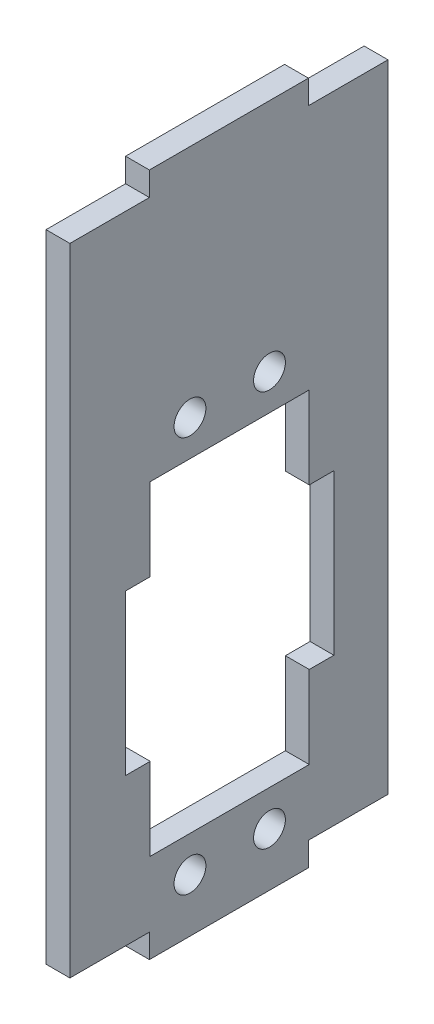
SolidWorks part; units mm, degrees
ref_plane "Plan de face" through (0, 0, 0) normal (0, 0, 1) x (1, 0, 0)
ref_plane "Plan de dessus" through (0, 0, 0) normal (0, 1, 0) x (1, 0, 0)
ref_plane "Plan de droite" through (0, 0, 0) normal (1, 0, 0) x (0, 0, -1)
ref_plane "Plan1" through (3, 0, 0) normal (1, 0, 0) x (0, 0, -1)
sketch "Esquisse1" plane through (3, 0, 0) normal (1, 0, 0) x (0, 0, -1)
  line L12 (-31.5038, 89.2756) -> (-31.5038, 86.2756)
  line L13 (-31.5038, 86.2756) -> (-41.5038, 86.2756)
  line L14 (-41.5038, 86.2756) -> (-41.5038, 6.2756)
  line L15 (-41.5038, 6.2756) -> (-31.5038, 6.2756)
  line L16 (-31.5038, 6.2756) -> (-31.5038, 3.2756)
  line L17 (-31.5038, 3.2756) -> (-11.5038, 3.2756)
  line L18 (-11.5038, 3.2756) -> (-11.5038, 6.2756)
  line L19 (-11.5038, 6.2756) -> (-1.5038, 6.2756)
  line L20 (-1.5038, 6.2756) -> (-1.5038, 86.2756)
  line L21 (-1.5038, 86.2756) -> (-11.5038, 86.2756)
  line L22 (-11.5038, 86.2756) -> (-11.5038, 89.2756)
  line L23 (-11.5038, 89.2756) -> (-31.5038, 89.2756)
  dimension "D2" = 80
  dimension "D3" = 80
  dimension "D4" = 20
  dimension "D5" = 10
  dimension "D6" = 10
  dimension "D7" = 3
  dimension "D8" = 3
  dimension "D13" = 20
  dimension "D14" = 3
  dimension "D15" = 10
  dimension "D16" = 10
  dimension "D17" = 3
extrude "Boss.-Extru.1" add sketch "Esquisse1" against normal blind 3
sketch "Esquisse2" plane through (0, 0, 0) normal (-1, 0, 0) x (0, 0, 1)
  line L0 (11.4038, 44.9256) -> (11.4038, 55.2756)
  line L1 (11.4038, 55.2756) -> (31.4038, 55.2756)
  line L2 (31.4038, 55.2756) -> (31.4038, 44.9256)
  line L3 (31.4038, 44.9256) -> (34.5038, 44.9256)
  line L4 (34.5038, 44.9256) -> (34.5038, 24.8256)
  line L5 (34.5038, 24.8256) -> (31.4038, 24.8256)
  line L6 (31.4038, 24.8256) -> (31.4038, 14.4756)
  line L7 (31.4038, 14.4756) -> (11.4038, 14.4756)
  line L8 (11.4038, 14.4756) -> (11.4038, 24.8256)
  line L9 (11.4038, 24.8256) -> (8.3038, 24.8256)
  line L10 (8.3038, 24.8256) -> (8.3038, 44.9256)
  line L11 (8.3038, 44.9256) -> (11.4038, 44.9256)
  line L12 (11.5038, 89.2756) -> (31.5038, 89.2756) construction
  line L13 (41.5038, 86.2756) -> (41.5038, 6.2756) construction
  circle A0 centre (26.4038, 9.9756) radius 2
  circle A1 centre (16.4038, 59.7756) radius 2
  circle A2 centre (26.4038, 59.7756) radius 2
  circle A3 centre (16.4038, 9.9756) radius 2
  dimension "D1" = 4
  dimension "D2" = 4
  dimension "D3" = 4
  dimension "D4" = 4
  dimension "D5" = 4.5
  dimension "D6" = 4.5
  dimension "D7" = 4.5
  dimension "D8" = 4.5
  dimension "D9" = 10.35
  dimension "D10" = 20.1
  dimension "D11" = 10.35
  dimension "D12" = 3.1
  dimension "D13" = 3.1
  dimension "D14" = 3.1
  dimension "D15" = 20.1
  dimension "D16" = 10.35
  dimension "D17" = 3.1
  dimension "D18" = 10.35
  dimension "D19" = 5
  dimension "D20" = 5
  dimension "D21" = 5
  dimension "D22" = 5
  dimension "D23" = 34
  dimension "D24" = 7
  dimension "D25" = 20
extrude "Enlèv. mat.-Extru.1" cut sketch "Esquisse2" against normal through all
